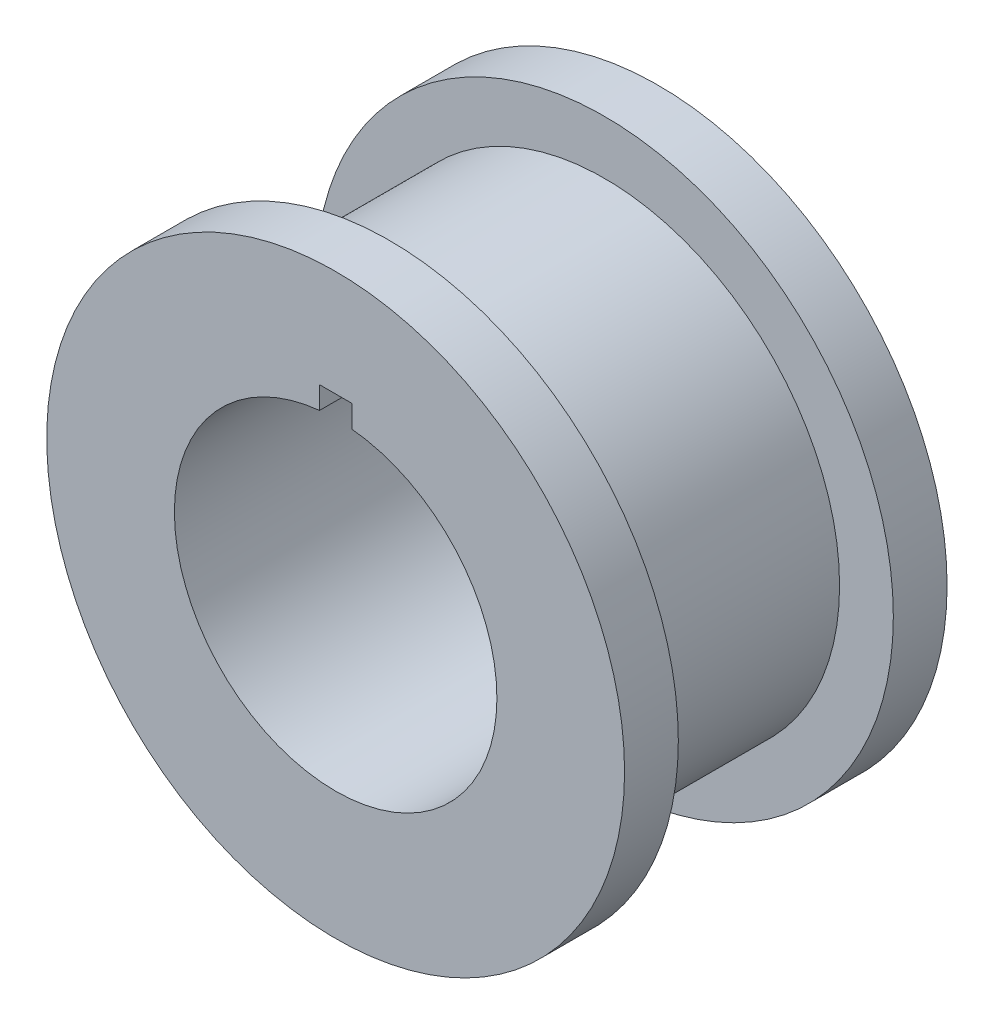
SolidWorks part; units mm, degrees
ref_plane "前视基准面" through (0, 0, 0) normal (0, 0, 1) x (1, 0, 0)
ref_plane "上视基准面" through (0, 0, 0) normal (0, 1, 0) x (1, 0, 0)
ref_plane "右视基准面" through (0, 0, 0) normal (1, 0, 0) x (0, 0, -1)
other "Configuration Table"
sketch "草图1" plane through (0, 0, 0) normal (0, 0, 1) x (1, 0, 0)
  circle A0 centre (0, 0) radius 21.875
  dimension "D1" = 43.75
extrude "凸台-拉伸1" add sketch "草图1" along normal mid plane 30
sketch "草图2" plane through (0, 0, 15) normal (0, 0, 1) x (1, 0, 0)
  line L0 (0, 0) -> (0, 31.3044) construction
  line L1 (0, 0) -> (10.9463, 30.0748) construction
  line L2 (0, 0) -> (2.3668, 30.0734) construction
  line L3 (0, 25) -> (8.0348, 22.0756) construction
  circle A0 centre (0, 0) radius 25 construction
  arc A1 (2.9173, 27.3448) -> (1.3963, 27.4645) centre (0, 0) ccw
  arc A2 (1.3963, 27.4645) -> (-0.5132, 21.869) centre (8.0348, 22.0756) ccw
  circle A3 centre (0, 0) radius 21.875 construction
  arc A4 (3.9279, 21.5195) -> (-0.5132, 21.869) centre (0, 0) ccw
  arc A5 (2.9173, 27.3448) -> (3.9279, 21.5195) centre (-4.4825, 23.0607) cw
  dimension "D1" = 55
  dimension "D2" = 50
  dimension "D3" = 20
  dimension "D4" = 4.5
pattern_circular "阵列(圆周)1" count 20 over 360 about axis through (0, 0, 15) along (0, 0, 1) of bodies 106 107
sketch "草图3" plane through (0, 0, 15) normal (0, 0, 1) x (1, 0, 0)
  circle A0 centre (0, 0) radius 15
  dimension "D1" = 30
extrude "切除-拉伸1" cut sketch "草图3" against normal through all
sketch "草图6" plane through (0, 0, 0) normal (0, 0, 1) x (1, 0, 0)
  line L1 (-1.5, 0) -> (1.5, 0)
  line L2 (-1.5, 0) -> (-1.5, 17)
  line L3 (-1.5, 17) -> (1.5, 17)
  line L4 (1.5, 0) -> (1.5, 17)
  point P4 (0, 0)
  dimension "D1" = 17
  dimension "D2" = 3
extrude "切除-拉伸4" cut sketch "草图6" along normal through all both and the other way through all
sketch "草图7" plane through (0, 0, 15) normal (0, 0, 1) x (1, 0, 0)
  circle A0 centre (0, 0) radius 21.875 construction
  circle A1 centre (0, 0) radius 21.875
  circle A2 centre (0, 0) radius 26.875
  dimension "D1" = 5
extrude "凸台-拉伸2" add sketch "草图7" against normal blind 5
mirror "镜向1" about plane through (0, 0, 0) normal (0, 0, 1) of "凸台-拉伸2"
